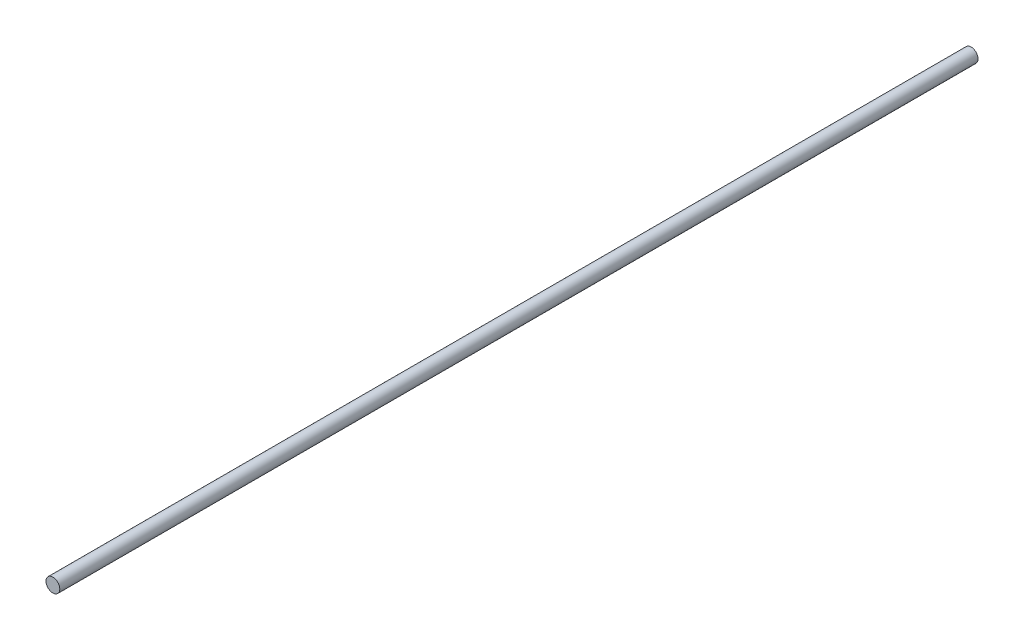
SolidWorks part; units mm, degrees
material "Oak"
ref_plane "Front Plane" through (0, 0, 0) normal (0, 0, 1) x (1, 0, 0)
ref_plane "Top Plane" through (0, 0, 0) normal (0, 1, 0) x (1, 0, 0)
ref_plane "Right Plane" through (0, 0, 0) normal (1, 0, 0) x (0, 0, -1)
sketch "Sketch1" plane through (0, 0, 0) normal (0, 0, 1) x (1, 0, 0)
  circle A0 centre (0, 0) radius 9.525
  dimension "D1" = 19.05
extrude "Boss-Extrude1" add sketch "Sketch1" along normal blind 1270
